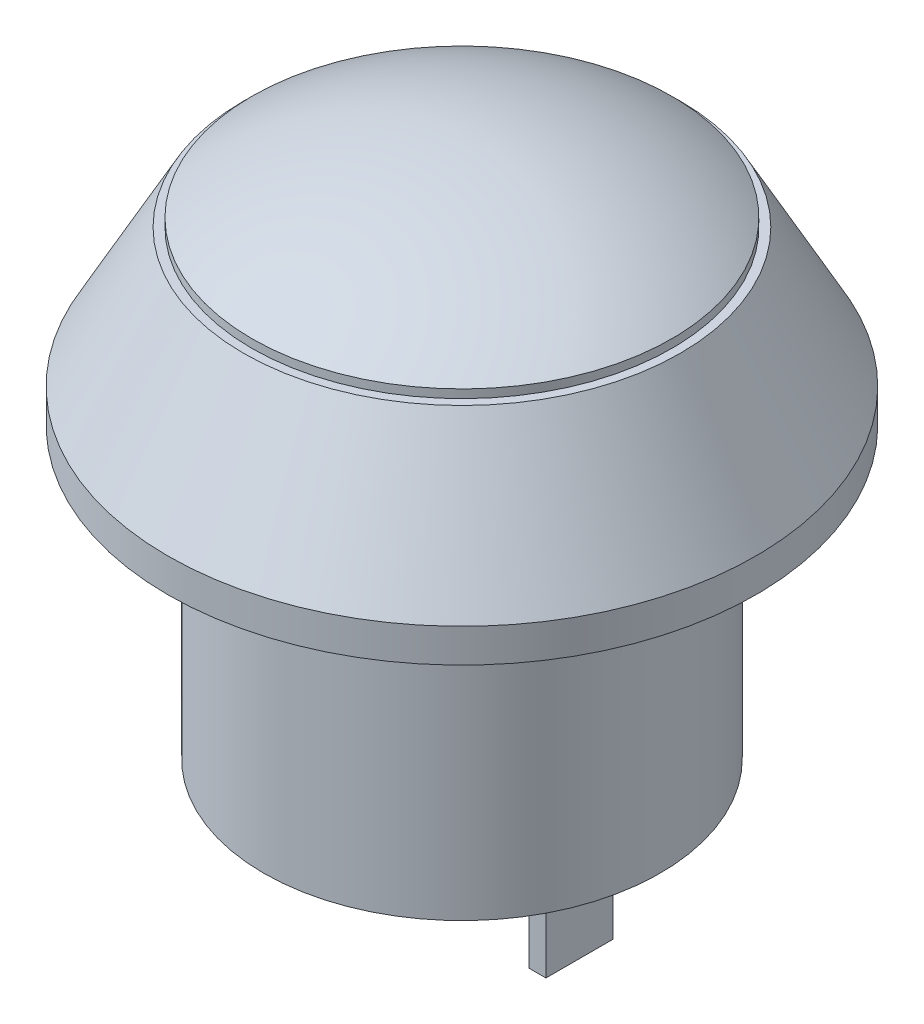
SolidWorks part; units mm, degrees
ref_plane "Front Plane" through (0, 0, 0) normal (0, 0, 1) x (1, 0, 0)
ref_plane "Top Plane" through (0, 0, 0) normal (0, 1, 0) x (1, 0, 0)
ref_plane "Right Plane" through (0, 0, 0) normal (1, 0, 0) x (0, 0, -1)
sketch "Sketch1" plane through (0, 0, 0) normal (0, 0, 1) x (1, 0, 0)
  line L0 (0, 0) -> (-8.75, 0)
  line L1 (-8.75, 0) -> (-8.75, 1)
  line L2 (-8.75, 1) -> (-6.5, 5.1)
  line L3 (-6.5, 5.1) -> (-6.25, 5.1)
  line L6 (-6.25, 5.1) -> (-6.25, 5.35)
  line L7 (0, 7.3) -> (0, 0) construction
  line L8 (0, 0) -> (0, 7.3)
  arc A1 (-6.25, 5.35) -> (0, 7.3) centre (0, -3.691) cw
  dimension "D1" = 8.75
  dimension "D2" = 5.1
  dimension "D3" = 6.5
  dimension "D4" = 1
  dimension "D6" = 0.25
  dimension "D5" = 7.3
revolve "Revolve1" add sketch "Sketch1" angle 360 about L7
sketch "Sketch2" plane through (0, 0, 0) normal (0, -1, 0) x (1, 0, 0)
  circle A0 centre (0, 0) radius 5.9
  dimension "D1" = 11.8
extrude "Boss-Extrude1" add sketch "Sketch2" along normal blind 8.6
sketch "Sketch3" plane through (0, -8.6, 0) normal (0, -1, 0) x (1, 0, 0)
  line L0 (0, 0) -> (-3, 0) construction
  line L1 (-3.5, 1) -> (-3, 1)
  line L2 (-3.5, 1) -> (-3.5, -1)
  line L3 (-3.5, -1) -> (-3, -1)
  line L4 (-3, 1) -> (-3, -1)
  line L5 (3, 1) -> (3.5, 1)
  line L6 (3, 1) -> (3, -1)
  line L7 (3, -1) -> (3.5, -1)
  line L8 (3.5, 1) -> (3.5, -1)
  line L9 (0, 0) -> (3, 0) construction
  point P11 (-3.25, -1)
  point P13 (3.25, -1)
  point P14 (0, 0)
  point P15 (0, 0)
  point P16 (-3, 0)
  point P17 (3, 0)
  dimension "D1" = 6.5
  dimension "D2" = 0.5
  dimension "D3" = 2
extrude "Boss-Extrude2" add sketch "Sketch3" along normal blind 3.4 contours L2 L3 L4 L1 | L6 L7 L8 L5
equation "\"D1@Sketch1\"=17.5/2"
equation "\"D1@Boss-Extrude2\"=12-8.6"
